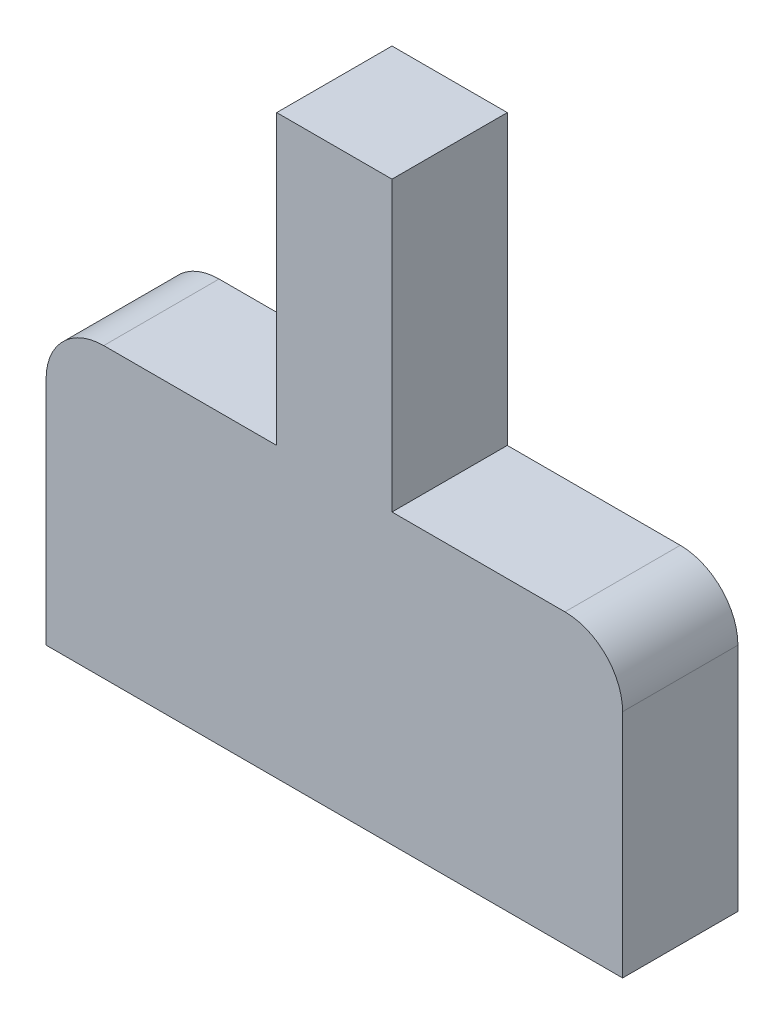
SolidWorks part; units mm, degrees
ref_plane "Front Plane" through (0, 0, 0) normal (0, 0, 1) x (1, 0, 0)
ref_plane "Top Plane" through (0, 0, 0) normal (0, 1, 0) x (1, 0, 0)
ref_plane "Right Plane" through (0, 0, 0) normal (1, 0, 0) x (0, 0, -1)
sketch "Sketch1" plane through (0, 0, 0) normal (0, 0, 1) x (1, 0, 0)
  line L0 (-40, 0) -> (60, 0)
  line L1 (60, 0) -> (60, 40)
  line L2 (-40, 0) -> (-40, 40)
  line L3 (-30, 50) -> (0, 50)
  line L4 (20, 50) -> (20, 100)
  line L5 (20, 100) -> (0, 100)
  line L6 (0, 100) -> (0, 50)
  line L7 (20, 50) -> (50, 50)
  arc A0 (-30, 50) -> (-40, 40) centre (-30, 40) ccw
  arc A1 (60, 40) -> (50, 50) centre (50, 40) ccw
  point P8 (0, 0)
  point P14 (10, 0)
  point P15 (10, 100)
  point P16 (0, 0)
  point P17 (-37.0711, 47.0711)
  dimension "D1" = 10
  dimension "D7" = 7.0711
  dimension "D2" = 50
  dimension "D3" = 50
  dimension "D4" = 50
  dimension "D5" = 40
  dimension "D6" = 100
extrude "Boss-Extrude1" add sketch "Sketch1" along normal blind 20
